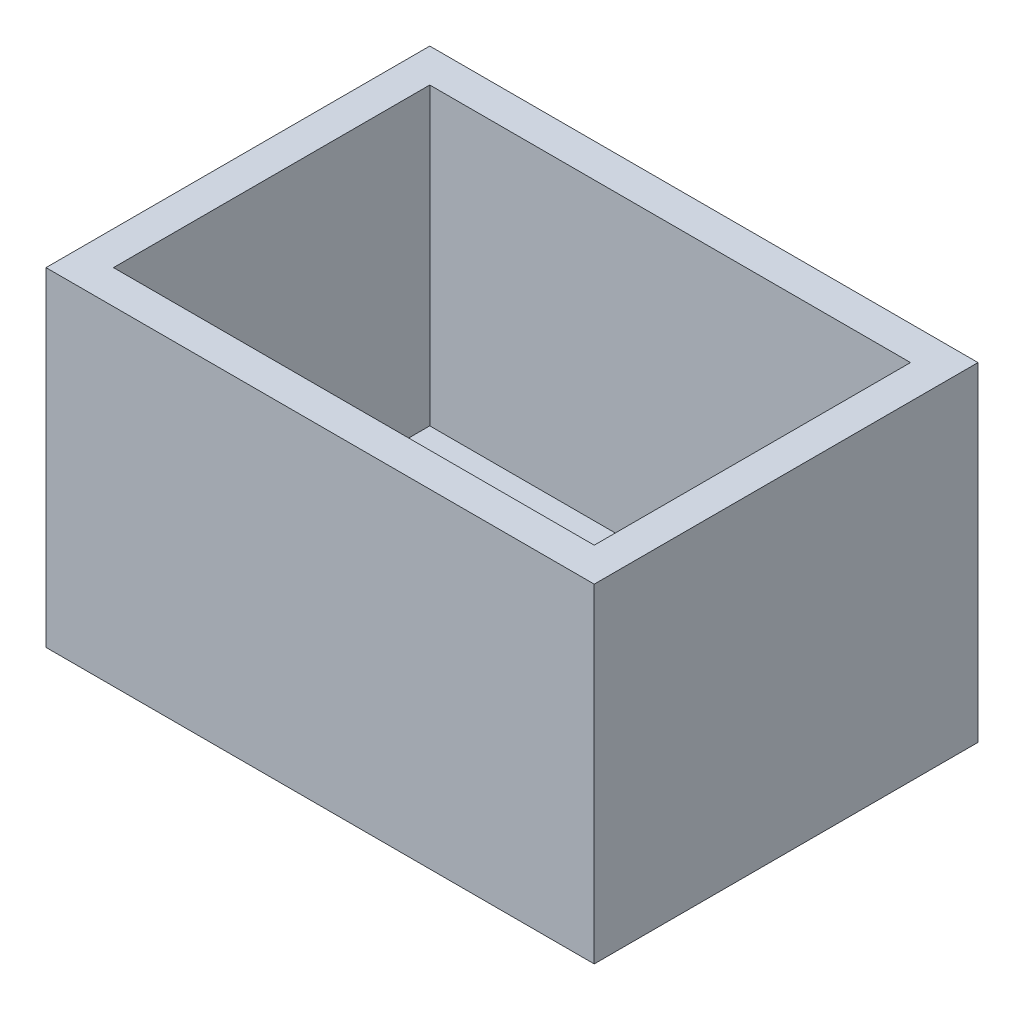
SolidWorks part; units mm, degrees
ref_plane "Front Plane" through (0, 0, 0) normal (0, 0, 1) x (1, 0, 0)
ref_plane "Top Plane" through (0, 0, 0) normal (0, 1, 0) x (1, 0, 0)
ref_plane "Right Plane" through (0, 0, 0) normal (1, 0, 0) x (0, 0, -1)
sketch "Sketch1" plane through (0, 0, 0) normal (0, 1, 0) x (1, 0, 0)
  line L1 (-16.25, 11.375) -> (16.25, 11.375)
  line L2 (-16.25, 11.375) -> (-16.25, -11.375)
  line L3 (-16.25, -11.375) -> (16.25, -11.375)
  line L4 (16.25, 11.375) -> (16.25, -11.375)
  line L5 (-16.25, 11.375) -> (16.25, -11.375) construction
  line L6 (-16.25, -11.375) -> (16.25, 11.375) construction
  point P0 (0, 0)
  dimension "D1" = 32.5
  dimension "D2" = 22.75
extrude "Boss-Extrude1" add sketch "Sketch1" along normal blind 19.5
shell "Shell1" thickness 2
